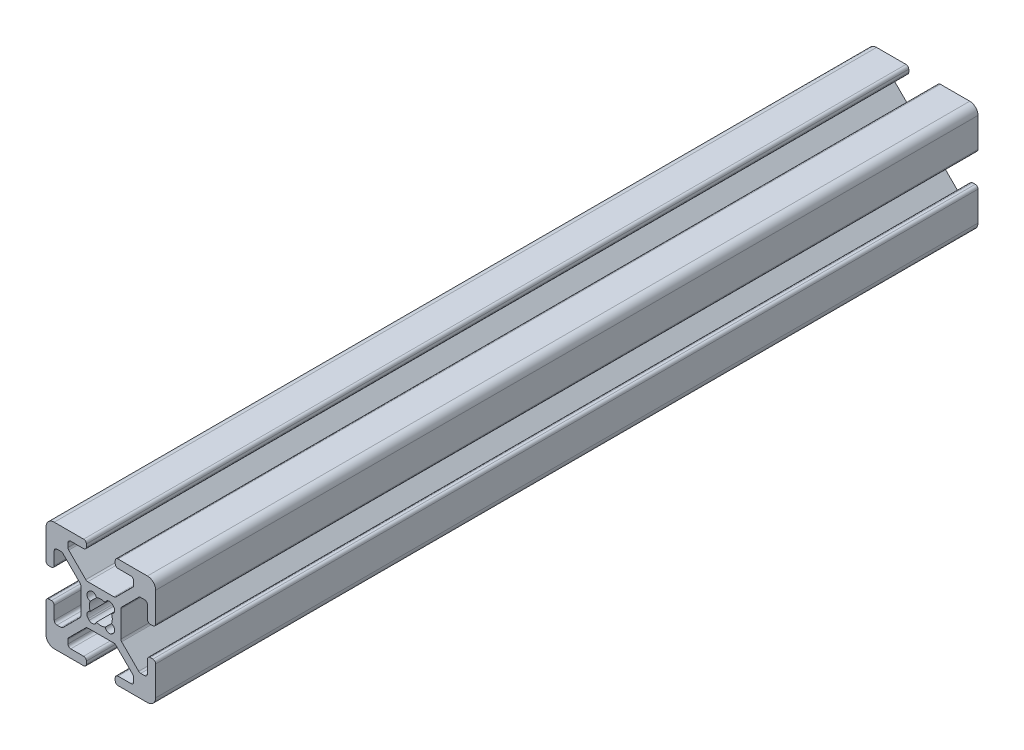
SolidWorks part; units mm, degrees
material "1060 Alloy"
ref_plane "Front Plane" through (0, 0, 0) normal (0, 0, 1) x (1, 0, 0)
ref_plane "Top Plane" through (0, 0, 0) normal (0, 1, 0) x (1, 0, 0)
ref_plane "Right Plane" through (0, 0, 0) normal (1, 0, 0) x (0, 0, -1)
sketch "Sketch2" plane through (0, 0, 0) normal (0, 0, 1) x (1, 0, 0)
  line L0 (-10, -3.138) -> (-10, -8.5)
  line L1 (-8.5, -10) -> (-3.138, -10)
  line L2 (-2.63, -9.492) -> (-2.63, -9.008)
  line L3 (-3.138, -8.5) -> (-5.487, -8.5)
  line L4 (-5.995, -7.992) -> (-5.995, -7.2662)
  line L5 (-5.8462, -6.907) -> (-2.743, -3.8038)
  line L6 (-2.3838, -3.655) -> (2.3841, -3.655)
  line L7 (2.7433, -3.8038) -> (5.8462, -6.9067)
  line L8 (5.995, -7.2659) -> (5.995, -7.992)
  line L9 (5.487, -8.5) -> (3.138, -8.5)
  line L10 (2.63, -9.008) -> (2.63, -9.492)
  line L11 (3.138, -10) -> (8.5, -10)
  line L12 (10, -8.5) -> (10, -3.138)
  line L13 (9.492, -2.63) -> (9.008, -2.63)
  line L14 (8.5, -3.138) -> (8.5, -5.487)
  line L15 (7.992, -5.995) -> (7.2662, -5.995)
  line L16 (6.907, -5.8462) -> (3.8038, -2.743)
  line L17 (3.655, -2.3838) -> (3.655, 2.3841)
  line L18 (3.8038, 2.7433) -> (6.9067, 5.8462)
  line L19 (7.2659, 5.995) -> (7.992, 5.995)
  line L20 (8.5, 5.487) -> (8.5, 3.138)
  line L21 (9.008, 2.63) -> (9.492, 2.63)
  line L22 (10, 3.138) -> (10, 8.5)
  line L23 (8.5, 10) -> (3.138, 10)
  line L24 (2.63, 9.492) -> (2.63, 9.008)
  line L25 (3.138, 8.5) -> (5.487, 8.5)
  line L26 (5.995, 7.992) -> (5.995, 7.2662)
  line L27 (5.8462, 6.907) -> (2.743, 3.8038)
  line L28 (2.3838, 3.655) -> (-2.3841, 3.655)
  line L29 (-2.7433, 3.8038) -> (-5.8462, 6.9067)
  line L30 (-5.995, 7.2659) -> (-5.995, 7.992)
  line L31 (-5.487, 8.5) -> (-3.138, 8.5)
  line L32 (-2.63, 9.008) -> (-2.63, 9.492)
  line L33 (-3.138, 10) -> (-8.5, 10)
  line L34 (-10, 8.5) -> (-10, 3.138)
  line L35 (-9.492, 2.63) -> (-9.008, 2.63)
  line L36 (-8.5, 3.138) -> (-8.5, 5.487)
  line L37 (-7.992, 5.995) -> (-7.2662, 5.995)
  line L38 (-6.907, 5.8462) -> (-3.8038, 2.743)
  line L39 (-3.655, 2.3838) -> (-3.655, -2.3841)
  line L40 (-3.8038, -2.7433) -> (-6.9067, -5.8462)
  line L41 (-7.2659, -5.995) -> (-7.992, -5.995)
  line L42 (-8.5, -5.487) -> (-8.5, -3.138)
  line L43 (-9.008, -2.63) -> (-9.492, -2.63)
  line L44 (-2.1245, 2.3045) -> (-2.3045, 2.1245)
  line L45 (2.3045, 2.1245) -> (2.1245, 2.3045)
  line L46 (2.1245, -2.3045) -> (2.3045, -2.1245)
  line L47 (-2.3045, -2.1245) -> (-2.1245, -2.3045)
  arc A0 (-10, -8.5) -> (-8.5, -10) centre (-8.5, -8.5) ccw
  arc A1 (-3.138, -10) -> (-2.63, -9.492) centre (-3.138, -9.492) ccw
  arc A2 (-2.63, -9.008) -> (-3.138, -8.5) centre (-3.138, -9.008) ccw
  arc A3 (-5.995, -7.992) -> (-5.487, -8.5) centre (-5.487, -7.992) ccw
  arc A4 (-5.8462, -6.907) -> (-5.995, -7.2662) centre (-5.487, -7.2662) ccw
  arc A5 (-2.3838, -3.655) -> (-2.743, -3.8038) centre (-2.3838, -4.163) ccw
  arc A6 (2.7433, -3.8038) -> (2.3841, -3.655) centre (2.3841, -4.163) ccw
  arc A7 (5.995, -7.2659) -> (5.8462, -6.9067) centre (5.487, -7.2659) ccw
  arc A8 (5.487, -8.5) -> (5.995, -7.992) centre (5.487, -7.992) ccw
  arc A9 (3.138, -8.5) -> (2.63, -9.008) centre (3.138, -9.008) ccw
  arc A10 (2.63, -9.492) -> (3.138, -10) centre (3.138, -9.492) ccw
  arc A11 (8.5, -10) -> (10, -8.5) centre (8.5, -8.5) ccw
  arc A12 (10, -3.138) -> (9.492, -2.63) centre (9.492, -3.138) ccw
  arc A13 (9.008, -2.63) -> (8.5, -3.138) centre (9.008, -3.138) ccw
  arc A14 (7.992, -5.995) -> (8.5, -5.487) centre (7.992, -5.487) ccw
  arc A15 (6.907, -5.8462) -> (7.2662, -5.995) centre (7.2662, -5.487) ccw
  arc A16 (3.655, -2.3838) -> (3.8038, -2.743) centre (4.163, -2.3838) ccw
  arc A17 (3.8038, 2.7433) -> (3.655, 2.3841) centre (4.163, 2.3841) ccw
  arc A18 (7.2659, 5.995) -> (6.9067, 5.8462) centre (7.2659, 5.487) ccw
  arc A19 (8.5, 5.487) -> (7.992, 5.995) centre (7.992, 5.487) ccw
  arc A20 (8.5, 3.138) -> (9.008, 2.63) centre (9.008, 3.138) ccw
  arc A21 (9.492, 2.63) -> (10, 3.138) centre (9.492, 3.138) ccw
  arc A22 (10, 8.5) -> (8.5, 10) centre (8.5, 8.5) ccw
  arc A23 (3.138, 10) -> (2.63, 9.492) centre (3.138, 9.492) ccw
  arc A24 (2.63, 9.008) -> (3.138, 8.5) centre (3.138, 9.008) ccw
  arc A25 (5.995, 7.992) -> (5.487, 8.5) centre (5.487, 7.992) ccw
  arc A26 (5.8462, 6.907) -> (5.995, 7.2662) centre (5.487, 7.2662) ccw
  arc A27 (2.3838, 3.655) -> (2.743, 3.8038) centre (2.3838, 4.163) ccw
  arc A28 (-2.7433, 3.8038) -> (-2.3841, 3.655) centre (-2.3841, 4.163) ccw
  arc A29 (-5.995, 7.2659) -> (-5.8462, 6.9067) centre (-5.487, 7.2659) ccw
  arc A30 (-5.487, 8.5) -> (-5.995, 7.992) centre (-5.487, 7.992) ccw
  arc A31 (-3.138, 8.5) -> (-2.63, 9.008) centre (-3.138, 9.008) ccw
  arc A32 (-2.63, 9.492) -> (-3.138, 10) centre (-3.138, 9.492) ccw
  arc A33 (-8.5, 10) -> (-10, 8.5) centre (-8.5, 8.5) ccw
  arc A34 (-10, 3.138) -> (-9.492, 2.63) centre (-9.492, 3.138) ccw
  arc A35 (-9.008, 2.63) -> (-8.5, 3.138) centre (-9.008, 3.138) ccw
  arc A36 (-7.992, 5.995) -> (-8.5, 5.487) centre (-7.992, 5.487) ccw
  arc A37 (-6.907, 5.8462) -> (-7.2662, 5.995) centre (-7.2662, 5.487) ccw
  arc A38 (-3.655, 2.3838) -> (-3.8038, 2.743) centre (-4.163, 2.3838) ccw
  arc A39 (-3.8038, -2.7433) -> (-3.655, -2.3841) centre (-4.163, -2.3841) ccw
  arc A40 (-7.2659, -5.995) -> (-6.9067, -5.8462) centre (-7.2659, -5.487) ccw
  arc A41 (-8.5, -5.487) -> (-7.992, -5.995) centre (-7.992, -5.487) ccw
  arc A42 (-8.5, -3.138) -> (-9.008, -2.63) centre (-9.008, -3.138) ccw
  arc A43 (-9.492, -2.63) -> (-10, -3.138) centre (-9.492, -3.138) ccw
  arc A44 (-1.9358, 0.8037) -> (-1.9358, -0.8037) centre (0, 0) ccw
  arc A45 (-2.3045, 2.1245) -> (-1.9358, 0.8037) centre (-1.748, 1.568) ccw
  arc A46 (-0.8037, 1.9358) -> (-2.1245, 2.3045) centre (-1.568, 1.748) ccw
  arc A47 (0.8037, 1.9358) -> (-0.8037, 1.9358) centre (0, 0) ccw
  arc A48 (2.1245, 2.3045) -> (0.8037, 1.9358) centre (1.568, 1.748) ccw
  arc A49 (1.9358, 0.8037) -> (2.3045, 2.1245) centre (1.748, 1.568) ccw
  arc A50 (1.9358, -0.8037) -> (1.9358, 0.8037) centre (0, 0) ccw
  arc A51 (2.3045, -2.1245) -> (1.9358, -0.8037) centre (1.748, -1.568) ccw
  arc A52 (0.8037, -1.9358) -> (2.1245, -2.3045) centre (1.568, -1.748) ccw
  arc A53 (-0.8037, -1.9358) -> (0.8037, -1.9358) centre (0, 0) ccw
  arc A54 (-2.1245, -2.3045) -> (-0.8037, -1.9358) centre (-1.568, -1.748) ccw
  arc A55 (-1.9358, -0.8037) -> (-2.3045, -2.1245) centre (-1.748, -1.568) ccw
extrude "Boss-Extrude1" add sketch "Sketch2" against normal blind 150
